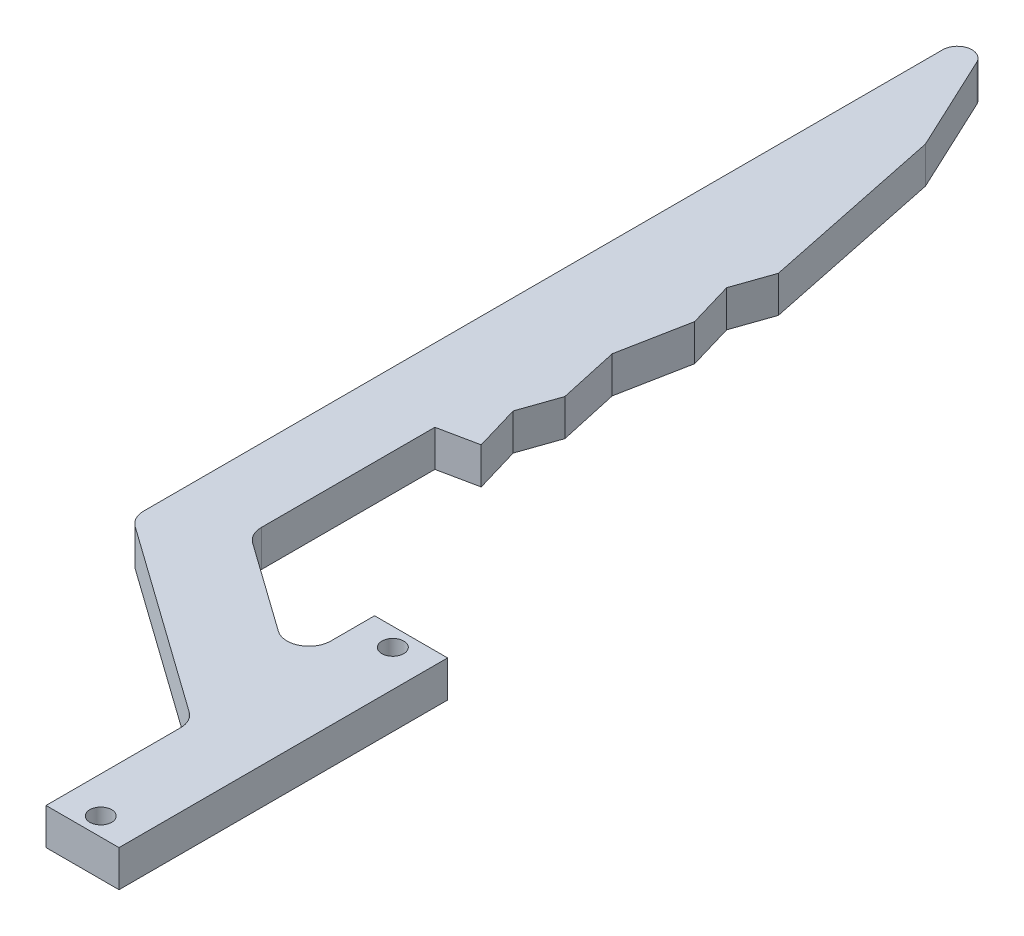
SolidWorks part; units mm, degrees
ref_plane "Front Plane" through (0, 0, 0) normal (0, 0, 1) x (1, 0, 0)
ref_plane "Top Plane" through (0, 0, 0) normal (0, 1, 0) x (1, 0, 0)
ref_plane "Right Plane" through (0, 0, 0) normal (1, 0, 0) x (0, 0, -1)
sketch "Sketch1" plane through (0, 0, 0) normal (0, 1, 0) x (1, 0, 0)
  line L1 (-5, 22.5) -> (5, 22.5)
  line L2 (-5, 22.5) -> (-5, -22.5)
  line L3 (-5, -22.5) -> (5, -22.5)
  line L4 (5, 22.5) -> (5, -22.5)
  line L5 (-5, 22.5) -> (5, -22.5) construction
  line L6 (-5, -22.5) -> (5, 22.5) construction
  point P0 (0, 0)
  dimension "D1" = 10
  dimension "D2" = 45
extrude "Boss-Extrude1" add sketch "Sketch1" along normal blind 5
sketch "Sketch2" plane through (0, 5, 0) normal (0, 1, 0) x (1, 0, 0)
  line L0 (5, 22.5) -> (-5, 22.5) construction
  circle A0 centre (0, -20) radius 1.5
  circle A1 centre (0, 20) radius 1.5
  dimension "D1" = 3
  dimension "D2" = 40
  dimension "D3" = 2.5
extrude "Cut-Extrude1" cut sketch "Sketch2" against normal blind 8
sketch "Sketch6" plane through (0, 5, 0) normal (0, 1, 0) x (1, 0, 0)
  line L0 (-5, -2.5233) -> (-33.2276, 17.5788)
  line L1 (-5, 22.5) -> (-5, -22.5) construction
  line L2 (-33.2276, 17.5788) -> (-33.2276, 104.5389)
  line L3 (-33.2276, 104.5389) -> (-23.2276, 104.5389)
  line L4 (-23.2276, 104.5389) -> (-23.2276, 23.6709)
  line L5 (-23.2276, 23.6709) -> (-5, 10.6902)
  line L6 (-5, 10.6902) -> (-5, -2.5233)
  point P8 (0, 0)
  point P9 (-16.8172, 15.1533)
  line M11 (-5, 22.5) -> (-5, -22.5)
  dimension "D1" = 10
extrude "Boss-Extrude3" add sketch "Sketch6" against normal up to surface (5 mm away) contours L5 L4 L3 L2 L0 M11 up to face at (0, 0, 21.5)
sketch "Sketch7" plane through (0, 5, 0) normal (0, 1, 0) x (1, 0, 0)
  line L0 (-23.2276, 116.1741) -> (-17.9701, 90.769)
  line L1 (-17.9701, 90.769) -> (-19.8005, 85.5177)
  line L2 (-19.8005, 85.5177) -> (-17.9701, 79.3102)
  line L3 (-17.9701, 79.3102) -> (-19.8005, 69.8509)
  line L4 (-19.8005, 69.8509) -> (-17.9701, 61.5326)
  line L5 (-17.9701, 61.5326) -> (-19.8005, 56.2813)
  line L6 (-19.8005, 56.2813) -> (-17.9701, 50.0738)
  line L7 (-17.9701, 50.0738) -> (-23.2276, 48.9857)
  line L8 (-23.2276, 104.5389) -> (-23.2276, 23.6709) construction
  line L10 (-23.2276, 48.9857) -> (-23.2276, 104.5389)
  line L11 (-23.2276, 104.5389) -> (-33.2276, 104.5389)
  line L12 (-33.2276, 104.5389) -> (-33.2276, 137.5316)
  line L13 (-33.2276, 137.5316) -> (-23.2276, 116.1741)
  point P7 (-33.2276, 137.5316)
extrude "Boss-Extrude4" add sketch "Sketch7" against normal up to surface (5 mm away) up to face at (0, 0, 21.5)
fillet "Fillet1" radius 2 1 edges at (-33.2276, 2.5, -137.5316)
fillet "Fillet2" radius 3 3 edges at (-5, 2.5, -10.6902) (-23.2276, 2.5, -23.6709) (-5, 2.5, 2.5233)
fillet "Fillet3" radius 3 1 edges at (-33.2276, 2.5, -17.5788)
